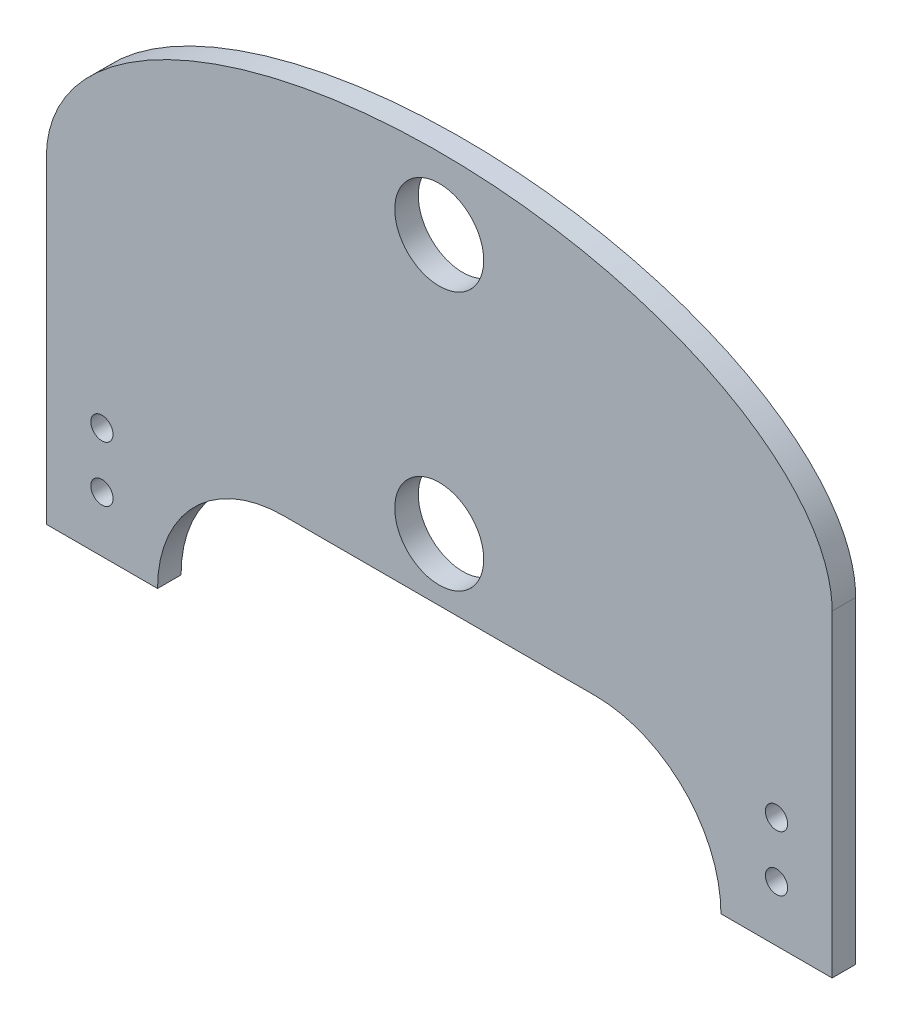
SolidWorks part; units mm, degrees
ref_plane "Front Plane" through (0, 0, 0) normal (0, 0, 1) x (1, 0, 0)
ref_plane "Top Plane" through (0, 0, 0) normal (0, 1, 0) x (1, 0, 0)
ref_plane "Right Plane" through (0, 0, 0) normal (1, 0, 0) x (0, 0, -1)
sketch "Sketch1" plane through (0, 0, 0) normal (0, 0, 1) x (1, 0, 0)
  line L0 (53, 0) -> (53, 25.4)
  line L1 (0, 0) -> (106, 0)
  line L2 (0, 0) -> (0, 70)
  line L3 (0, 70) -> (106, 70)
  line L4 (106, 0) -> (106, 70)
  line L5 (0, 0) -> (15, 0)
  line L6 (106, 0) -> (91, 0)
  line L7 (53, 19.4) -> (53, 17.4)
  line L12 (15, 0) -> (91, 0)
  line L13 (15, 0) -> (15, 17)
  line L14 (91, 0) -> (91, 17)
  line L15 (15, 17) -> (91, 17)
  circle A0 centre (53, 25.4) radius 6
  circle A2 centre (74, 0) radius 17
  circle A4 centre (32, 0) radius 17
  circle A5 centre (53, 60.325) radius 6
  dimension "D4" = 2
  dimension "D5" = 17
  dimension "D7" = 34.925
  dimension "D1" = 106
  dimension "D2" = 70
  dimension "D3" = 25.4
extrude "Boss-Extrude1" add sketch "Sketch1" along normal blind 3.175
sketch "Sketch2" plane through (0, 0, 0) normal (0, 0, -1) x (-1, 0, 0)
  line L0 (-53, 60.325) -> (-53, 28.575)
  dimension "D1" = 31.75
sketch "Sketch4" plane through (0, 0, 0) normal (0, 0, -1) x (-1, 0, 0)
  line L0 (-98.5, 0) -> (-98.5, 7.5)
  line L1 (-91, 0) -> (-106, 0) construction
  line L2 (-98.5, 7.5) -> (-98.5, 15)
  line L3 (-7.5, 0) -> (-7.5, 7.5)
  line L4 (0, 0) -> (-15, 0) construction
  line L5 (-7.5, 7.5) -> (-7.5, 15)
  circle A0 centre (-7.5, 15) radius 1.5
  circle A1 centre (-7.5, 7.5) radius 1.5
  circle A2 centre (-98.5, 7.5) radius 1.5
  circle A3 centre (-98.5, 15) radius 1.5
  dimension "D1" = 7.5
  dimension "D2" = 7.5
  dimension "D3" = 7.5
  dimension "D4" = 7.5
extrude "Cut-Extrude2" cut sketch "Sketch4" against normal through all
sketch "Sketch6" plane through (0, 0, 0) normal (0, 0, -1) x (-1, 0, 0)
  line L0 (-53, 25.4) -> (-53, 60.325)
  line L1 (0, 0) -> (0, 70) construction
  ellipse E0 centre (-53, 42.8625) end of major axis (0, 42.8625) minor radius 27.1375
  line M7 (0, 0) -> (0, 70)
  line M8 (0, 70) -> (-106, 70)
  line M9 (-106, 70) -> (-106, 0)
extrude "Cut-Extrude4" cut sketch "Sketch6" against normal through all contours E0 M8 M9 | E0 M7 M8
